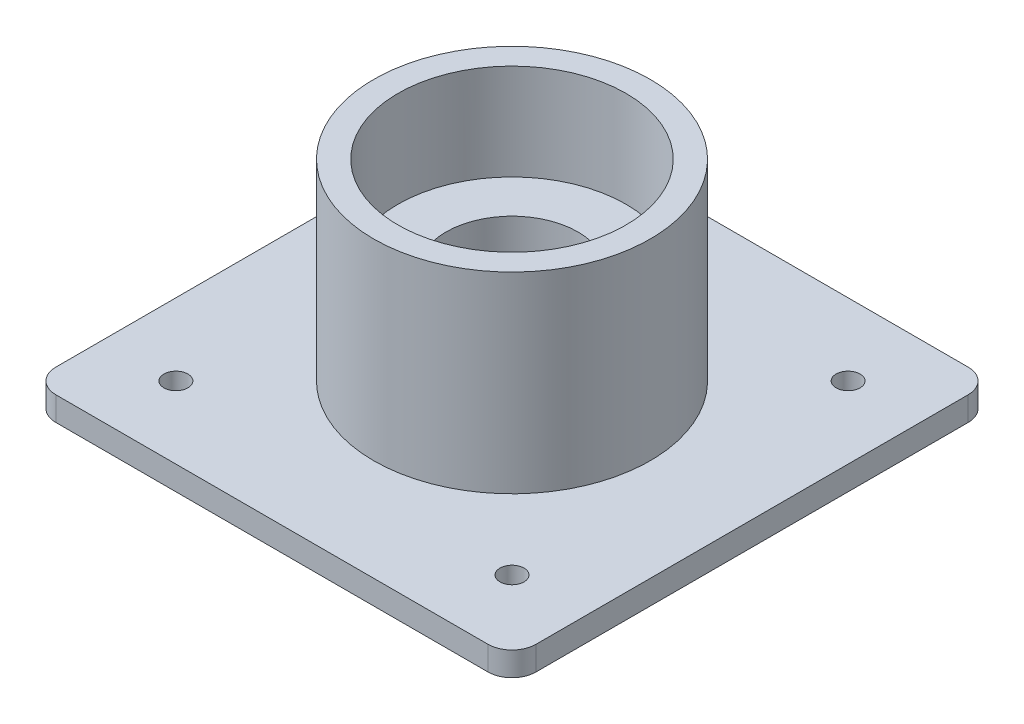
SolidWorks part; units mm, degrees
material "Plain Carbon Steel"
ref_plane "Front Plane" through (0, 0, 0) normal (0, 0, 1) x (1, 0, 0)
ref_plane "Top Plane" through (0, 0, 0) normal (0, 1, 0) x (1, 0, 0)
ref_plane "Right Plane" through (0, 0, 0) normal (1, 0, 0) x (0, 0, -1)
sketch "Sketch1" plane through (0, 0, 0) normal (0, 1, 0) x (1, 0, 0)
  circle A0 centre (0, 0) radius 17.4625
  circle A1 centre (0, 0) radius 30.1625
  dimension "D1" = 34.925
  dimension "D2" = 60.325
extrude "ID" add sketch "Sketch1" along normal blind 25.4
sketch "Sketch2" plane through (0, 0, 0) normal (0, -1, 0) x (1, 0, 0)
  circle A0 centre (0, 0) radius 30.1625
  circle A1 centre (0, 0) radius 36.576
  dimension "D1" = 60.325
  dimension "D2" = 73.152
extrude "OD" add sketch "Sketch2" against normal blind 50.8
sketch "Sketch3" plane through (0, 0, 0) normal (0, -1, 0) x (1, 0, 0)
  line L17 (-63.5, -63.5) -> (63.5, -63.5)
  line L18 (-63.5, -63.5) -> (-63.5, 63.5)
  line L19 (-63.5, 63.5) -> (63.5, 63.5)
  line L20 (63.5, -63.5) -> (63.5, 63.5)
  line L21 (-63.5, -63.5) -> (63.5, 63.5) construction
  line L22 (-63.5, 63.5) -> (63.5, -63.5) construction
  circle A1 centre (0, 0) radius 17.4625
  dimension "D4" = 34.925
  dimension "D1" = 127
extrude "Base" add sketch "Sketch3" along normal blind 6.35
fillet "Base corner fillet" radius 6.35 4 edges at (63.5, -3.175, -63.5) (-63.5, -3.175, 63.5) (-63.5, -3.175, -63.5) (63.5, -3.175, 63.5)
hole_wizard "1/4 (0.25) Diameter Hole1" positions "Sketch4" profile "Sketch5" hole size "1/4" standard "ANSI Inch" end condition through all
sketch "Sketch4" plane through (0, 0, 0) normal (0, 1, 0) x (1, 0, 0)
  line L0 (57.15, -63.5) -> (-57.15, -63.5) construction
  line L1 (-63.5, -57.15) -> (-63.5, 57.15) construction
  point P0 (-44.45, -44.45)
  dimension "D1" = 19.05
  dimension "D2" = 19.05
sketch "Sketch5" plane through (-44.45, 0, 44.45) normal (1, 0, 0) x (0, 0, 1)
  line L0 (0, 0) -> (0, 6.35)
  line L1 (0, 6.35) -> (3.175, 6.35)
  line L2 (3.175, 6.35) -> (3.175, 0)
  line L5 (3.175, 0) -> (0, 0)
  line L11 (0, -6.35) -> (0, 107.95) construction
  dimension "Thru Hole Dia." = 6.35
  dimension "Thru Hole Depth" = 6.35
pattern_circular "Bolt Pattern" count 4 over 360 about axis through (0, 0, 0) along (0, 1, 0) of "1/4 (0.25) Diameter Hole1"
